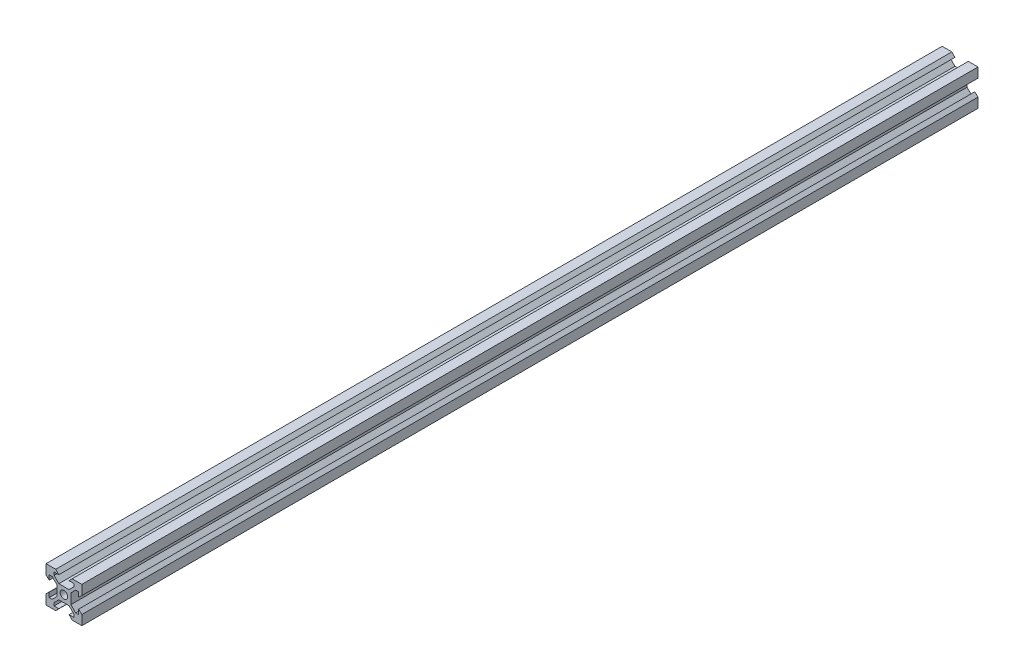
SolidWorks part; units mm, degrees
ref_plane "Front Plane" through (0, 0, 0) normal (0, 0, 1) x (1, 0, 0)
ref_plane "Top Plane" through (0, 0, 0) normal (0, 1, 0) x (1, 0, 0)
ref_plane "Right Plane" through (0, 0, 0) normal (1, 0, 0) x (0, 0, -1)
sketch "Sketch1" plane through (0, 0, 0) normal (0, 0, 1) x (1, 0, 0)
  line L0 (-4.58, 10) -> (-2.885, 8.2)
  line L1 (10, -10) -> (4.58, -10)
  line L2 (10, -10) -> (10, -4.58)
  line L3 (10, 10) -> (4.58, 10)
  line L4 (-10, -10) -> (-10, -4.58)
  line L5 (10, -10) -> (-10, 10) construction
  line L6 (10, 10) -> (-10, -10) construction
  line L7 (-2.8393, 3.9) -> (2.8393, 3.9)
  line L8 (-3.9, 2.8393) -> (-3.9, -2.8393)
  line L9 (-2.8393, -3.9) -> (2.8393, -3.9)
  line L10 (3.9, 2.8393) -> (3.9, -2.8393)
  line L11 (-3.9, 3.9) -> (3.9, -3.9) construction
  line L12 (-3.9, -3.9) -> (3.9, 3.9) construction
  line L13 (4.58, 10) -> (2.885, 8.2)
  line L14 (10, 4.58) -> (10, 10)
  line L15 (-5.5, 8.2) -> (-2.885, 8.2)
  line L16 (-8.2, 5.5) -> (-8.2, 2.885)
  line L17 (-5.5, -8.2) -> (-2.885, -8.2)
  line L18 (8.2, 5.5) -> (8.2, 2.885)
  line L19 (-8.2, 8.2) -> (8.2, -8.2) construction
  line L20 (-8.2, -8.2) -> (8.2, 8.2) construction
  line L21 (10, 4.58) -> (8.2, 2.885)
  line L22 (10, -4.58) -> (8.2, -2.885)
  line L23 (4.58, -10) -> (2.885, -8.2)
  line L24 (-4.58, -10) -> (-2.885, -8.2)
  line L25 (-10, -4.58) -> (-8.2, -2.885)
  line L26 (-10, 4.58) -> (-8.2, 2.885)
  line L27 (0, 14.7958) -> (0, -12.2524) construction
  line L28 (-5.5, 8.2) -> (-5.5, 6.5607)
  line L29 (5.5, 8.2) -> (5.5, 6.5607)
  line L30 (-5.5, 6.5607) -> (-2.8393, 3.9)
  line L31 (2.8393, 3.9) -> (5.5, 6.5607)
  line L32 (-4.58, 10) -> (-10, 10)
  line L33 (2.885, 8.2) -> (5.5, 8.2)
  line L34 (8.2, -2.885) -> (8.2, -5.5)
  line L35 (2.885, -8.2) -> (5.5, -8.2)
  line L36 (-4.58, -10) -> (-10, -10)
  line L37 (-8.2, -2.885) -> (-8.2, -5.5)
  line L38 (-10, 4.58) -> (-10, 10)
  line L39 (8.2, 5.5) -> (6.5607, 5.5)
  line L40 (6.5607, 5.5) -> (3.9, 2.8393)
  line L41 (3.9, -2.8393) -> (6.5607, -5.5)
  line L42 (8.2, -5.5) -> (6.5607, -5.5)
  line L43 (5.5, -8.2) -> (5.5, -6.5607)
  line L44 (5.5, -6.5607) -> (2.8393, -3.9)
  line L45 (-2.8393, -3.9) -> (-5.5, -6.5607)
  line L46 (-5.5, -8.2) -> (-5.5, -6.5607)
  line L47 (-8.2, -5.5) -> (-6.5607, -5.5)
  line L48 (-6.5607, -5.5) -> (-3.9, -2.8393)
  line L49 (-3.9, 2.8393) -> (-6.5607, 5.5)
  line L50 (-8.2, 5.5) -> (-6.5607, 5.5)
  circle A0 centre (0, 0) radius 2.1
  point P0 (0, 0)
  point P35 (0, 0)
  point P62 (0, 0)
  dimension "D3" = 4.2
  dimension "D1" = 20
  dimension "D4" = 9.16
  dimension "D5" = 9.16
  dimension "D6" = 1.8
  dimension "D7" = 6.1
  dimension "D8" = 5.77
  dimension "D10" = 5.5
  dimension "D11" = 5.5
  dimension "D12" = 1.5
  dimension "D13" = 1.5
  dimension "D14" = 5.77
  dimension "D15" = 20
  dimension "D9" = 4
extrude "Boss-Extrude1" add sketch "Sketch1" along normal blind 500
